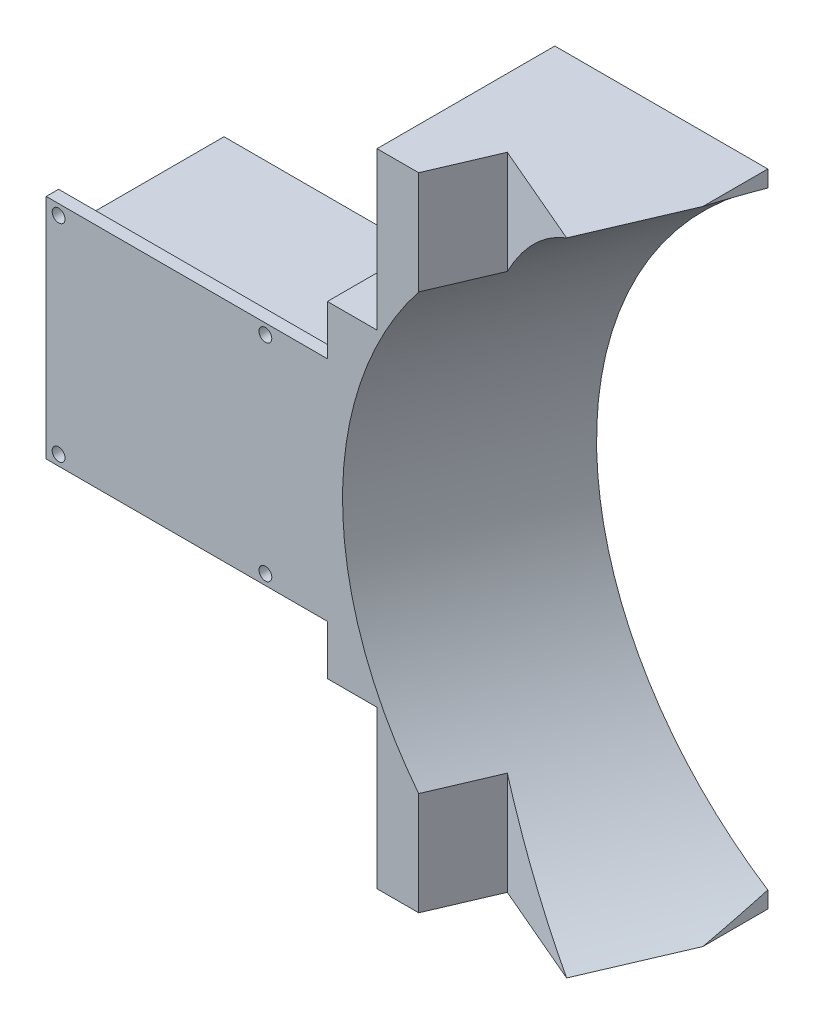
SolidWorks part; units mm, degrees
material "PTFE(普通)"
ref_plane "前视基准面" through (0, 0, 0) normal (0, 0, 1) x (1, 0, 0)
ref_plane "上视基准面" through (0, 0, 0) normal (0, 1, 0) x (1, 0, 0)
ref_plane "右视基准面" through (0, 0, 0) normal (1, 0, 0) x (0, 0, -1)
other "Configuration Table"
sketch "草图1" plane through (0, 0, 0) normal (0, 0, 1) x (1, 0, 0)
  line L1 (40, -27.5) -> (-40, -27.5)
  line L2 (40, -27.5) -> (40, 27.5)
  line L3 (40, 27.5) -> (-40, 27.5)
  line L4 (-40, -27.5) -> (-40, 27.5)
  line L5 (40, -27.5) -> (-40, 27.5) construction
  line L6 (40, 27.5) -> (-40, -27.5) construction
  point P0 (0, 0)
  dimension "D1" = 40
  dimension "D2" = 27.5
extrude "凸台-拉伸1" add sketch "草图1" along normal blind 3
sketch "草图2" plane through (0, 0, 0) normal (0, 0, -1) x (-1, 0, 0)
  line L0 (-40, 27.5) -> (40, 27.5) construction
  line L1 (40, -27.5) -> (-40, -27.5) construction
  line L2 (40, 27.5) -> (40, -27.5) construction
  line L3 (37, 25) -> (37, -25) construction
  circle A0 centre (37, 25) radius 1.55
  circle A1 centre (37, -25) radius 1.55
  circle A2 centre (-13, 25) radius 1.55
  circle A3 centre (-13, -25) radius 1.55
  dimension "D1" = 3.1
  dimension "D2" = 3.1
  dimension "D3" = 3.1
  dimension "D4" = 3.1
  dimension "D5" = 2.5
  dimension "D6" = 2.5
  dimension "D7" = 3
  dimension "D8" = 50
extrude "切除-拉伸1" cut sketch "草图2" against normal blind 24.5 contours A3 | A1 | A0 | A2
sketch "草图3" plane through (40, 0, 0) normal (1, 0, 0) x (0, 0, -1)
  line L1 (-3, 27.5) -> (0, 27.5)
  line L2 (-3, 27.5) -> (-3, -27.5)
  line L3 (-3, -27.5) -> (0, -27.5)
  line L4 (0, 27.5) -> (0, -27.5)
extrude "凸台-拉伸2" add sketch "草图3" along normal blind 1.5 separate body
sketch "草图4" plane through (0, 0, 3) normal (0, 0, 1) x (1, 0, 0)
  line L0 (40, 0) -> (41.5, 0) construction
  line L1 (40, -27.5) -> (40, 27.5) construction
  line L2 (41.5, 27.5) -> (41.5, -27.5) construction
sketch "草图5" plane through (41.5, 0, 0) normal (1, 0, 0) x (0, 0, -1)
  line L1 (-3, 27.5) -> (0, 27.5)
  line L2 (-3, 27.5) -> (-3, -27.5)
  line L3 (-3, -27.5) -> (0, -27.5)
  line L4 (0, 27.5) -> (0, -27.5)
extrude "凸台-拉伸3" add sketch "草图5" along normal blind 50
sketch "草图6" plane through (0, 27.5, 0) normal (0, 1, 0) x (1, 0, 0)
  line L1 (40, 0) -> (91.5, 0)
  line L2 (40, 0) -> (40, -3)
  line L3 (40, -3) -> (91.5, -3)
  line L4 (91.5, 0) -> (91.5, -3)
extrude "凸台-拉伸4" add sketch "草图6" along normal blind 50
sketch "草图7" plane through (0, -27.5, 0) normal (0, -1, 0) x (1, 0, 0)
  line L0 (40, 3) -> (41.5, 3) construction
  line L1 (40, 3) -> (91.5, 3)
  line L2 (40, 3) -> (40, 0)
  line L3 (40, 0) -> (91.5, 0)
  line L4 (91.5, 3) -> (91.5, 0)
  line L5 (-40, 3) -> (91.5, 3) construction
extrude "凸台-拉伸5" add sketch "草图7" along normal blind 50
sketch "草图8" plane through (0, 0, 0) normal (0, 0, -1) x (-1, 0, 0)
  line L1 (-91.5, 77.5) -> (-40, 77.5)
  line L2 (-91.5, 77.5) -> (-91.5, -77.5)
  line L3 (-91.5, -77.5) -> (-40, -77.5)
  line L4 (-40, 77.5) -> (-40, -77.5)
extrude "凸台-拉伸6" add sketch "草图8" along normal blind 40
sketch "草图9" plane through (40, 0, 0) normal (-1, 0, 0) x (0, 0, 1)
  line L0 (-40, 39.5) -> (3, 39.5)
  line L1 (-40, -77.5) -> (-40, 77.5) construction
  line L2 (3, 77.5) -> (3, 27.5) construction
  line L3 (-40, -39.5) -> (3, -39.5)
  line L4 (3, -77.5) -> (3, -27.5) construction
  line L5 (-40, 77.5) -> (3, 77.5) construction
  line L6 (3, -77.5) -> (-40, -77.5) construction
  line L7 (-40, 39.5) -> (-40, -39.5)
  line L8 (3, 39.5) -> (3, 27.5)
  line L9 (3, 27.5) -> (0, 27.5)
  line L10 (0, 27.5) -> (0, -27.5)
  line L11 (0, -27.5) -> (3, -27.5)
  line L12 (3, -27.5) -> (3, -39.5)
  dimension "D1" = 38
  dimension "D2" = 38
extrude "凸台-拉伸7" add sketch "草图9" along normal blind 12
sketch "草图10" plane through (0, 77.5, 0) normal (0, 1, 0) x (1, 0, 0)
  line L0 (40, -3) -> (91.5, -3) construction
  line L2 (91.5, -3) -> (91.5, 40) construction
  line L3 (56.5, 12) -> (91.5, -3)
  line L4 (56.5, 12) -> (50.0714, -3)
  line L5 (50.0714, -3) -> (91.5, -3)
  point P0 (56.5, 12)
  dimension "D1" = 15
  dimension "D2" = 35
sketch "草图11" plane through (0, -77.5, 0) normal (0, -1, 0) x (1, 0, 0)
  line L0 (91.5, 3) -> (56.5, -12)
extrude "切除-拉伸2" cut sketch "草图10" against normal blind 184 contours L4 L5 L3
sketch "草图13" plane through (13.1121, 0, -30.5948) normal (-0.3939, 0, 0.9191) x (0.9191, 0, 0.3939)
  line L0 (85.2835, 77.5) -> (85.2835, -77.5) construction
  line L1 (85.2835, -77.5) -> (47.2047, -77.5) construction
  circle A0 centre (120.2835, 0) radius 90
  dimension "D1" = 35
  dimension "D2" = 180
  dimension "D3" = 77.5
extrude "切除-拉伸3" cut sketch "草图13" along normal mid plane 184
sketch "草图14" plane through (0, 0, 0) normal (0, 0, -1) x (-1, 0, 0)
  line L0 (40, 27.5) -> (40, -27.5) construction
  line L1 (40, 18.5) -> (-28, 18.5)
  line L2 (40, 18.5) -> (40, -18.5)
  line L3 (40, -18.5) -> (-28, -18.5)
  line L4 (-28, 18.5) -> (-28, -18.5)
  line L5 (-28, 39.5) -> (-28, -39.5) construction
  line L6 (-28, 27.5) -> (40, 27.5) construction
  line L7 (40, -27.5) -> (-28, -27.5) construction
  dimension "D1" = 9
  dimension "D2" = 9
sketch "草图15" plane through (28, 0, 0) normal (-1, 0, 0) x (0, 0, 1)
  line L2 (-40, 39.5) -> (-40, -39.5)
  line L3 (0, 18.5) -> (0, -18.5) construction
  dimension "D1" = 40
extrude "凸台-拉伸8" add sketch "草图14" along normal blind 40
